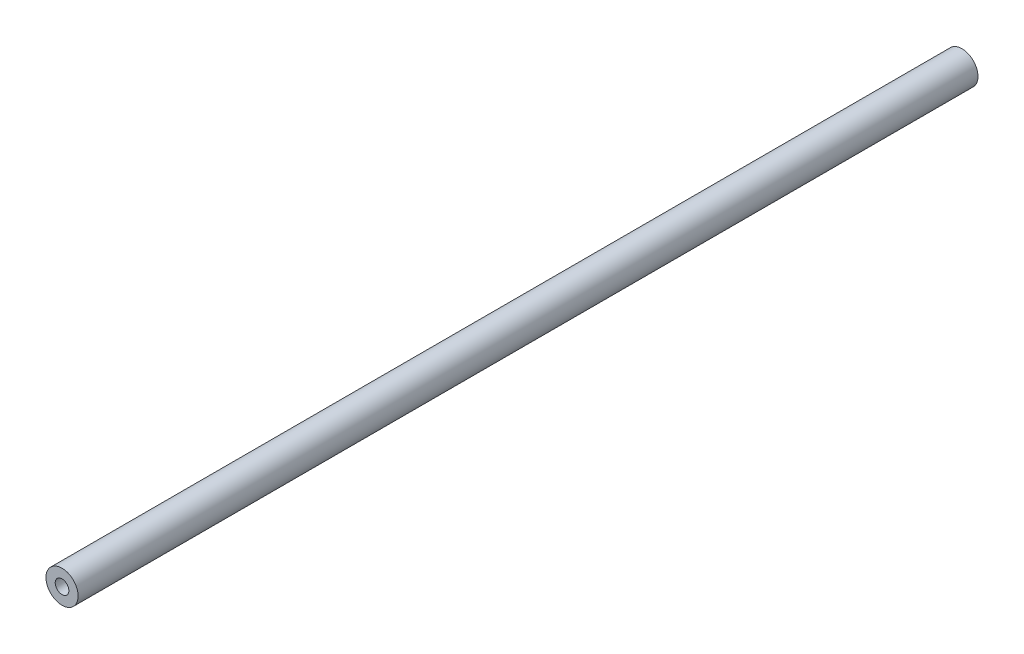
SolidWorks part; units mm, degrees
material "6061-T6 (SS)"
ref_plane "Front Plane" through (0, 0, 0) normal (0, 0, 1) x (1, 0, 0)
ref_plane "Top Plane" through (0, 0, 0) normal (0, 1, 0) x (1, 0, 0)
ref_plane "Right Plane" through (0, 0, 0) normal (1, 0, 0) x (0, 0, -1)
sketch "Sketch1" plane through (0, 0, 0) normal (0, 0, 1) x (1, 0, 0)
  circle A1 centre (0, 0) radius 4.7625
  dimension "D2" = 9.525
extrude "Boss-Extrude1" add sketch "Sketch1" along normal mid plane 266.7
hole_wizard "#10-32 Tapped Hole1" positions "3DSketch1" profile "Sketch2" tap size "#10-32" standard "ANSI Inch"
sketch3d "3DSketch1"
  line L0 (0, 0, 133.35) -> (0, 0, -133.35) construction
  point P0 (0, 0, 133.35)
  point P4 (0, 0, -133.35)
sketch "Sketch2" plane through (0, 0, 133.35) normal (1, 0, 0) x (0, -1, 0)
  line L0 (0, 0) -> (0, 13.2428)
  line L1 (0, 13.2428) -> (2.0193, 12.0294)
  line L2 (2.0193, 12.0294) -> (2.0193, 0)
  line L5 (2.0193, 0) -> (0, 0)
  line L10 (0, 13.2428) -> (-2.0193, 12.0294) construction
  line L11 (0, -6.35) -> (0, 107.95) construction
  dimension "Tap Drill Dia." = 4.0386
  dimension "Tap Drill Depth" = 12.0294
  dimension "Drill Angle" = 118
cosmetic thread "Hole Thread1"
cosmetic thread "Hole Thread2"
